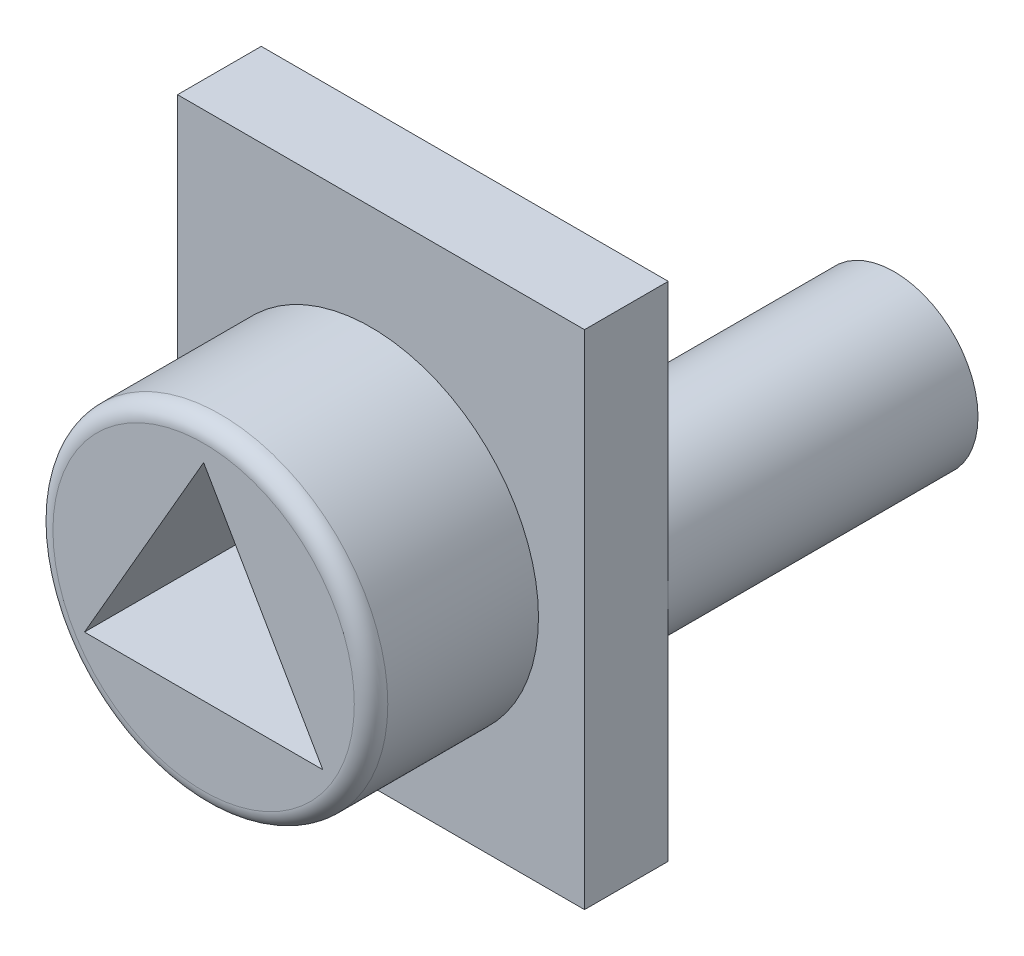
SolidWorks part; units mm, degrees
ref_plane "Спереди" through (0, 0, 0) normal (0, 0, 1) x (1, 0, 0)
ref_plane "Сверху" through (0, 0, 0) normal (0, 1, 0) x (1, 0, 0)
ref_plane "Справа" through (0, 0, 0) normal (1, 0, 0) x (0, 0, -1)
other "Configuration Table"
sketch "Эскиз1" plane through (0, 0, 0) normal (0, 0, 1) x (1, 0, 0)
  line L0 (-2.7384, -2.0301) -> (2.2616, -2.0301)
  line L1 (4.8616, -6) -> (4.8616, 6)
  line L2 (4.8616, 6) -> (-4.8616, 6)
  line L3 (-4.8616, 6) -> (-4.8616, -6)
  line L4 (-4.8616, -6) -> (4.8616, -6)
  line L5 (-0.2384, 2.3) -> (-2.7384, -2.0301)
  line L6 (2.2616, -2.0301) -> (-0.2384, 2.3)
  circle A0 centre (-0.2384, -0.5) radius 4
  circle A1 centre (2.8616, -0.5) radius 2
sketch "Эскиз2" plane through (0, 0, 0) normal (0, 0, 1) x (1, 0, 0)
  line L0 (-4.8616, -6) -> (4.8616, -6) construction
  line L1 (-4.8616, 6) -> (-4.8616, -6) construction
  line L2 (4.8616, 6) -> (-4.8616, 6) construction
  line L3 (4.8616, -6) -> (4.8616, 6) construction
  line L4 (-4.8616, -6) -> (4.8616, -6)
  line L5 (-4.8616, 6) -> (-4.8616, -6)
  line L6 (4.8616, 6) -> (-4.8616, 6)
  line L7 (4.8616, -6) -> (4.8616, 6)
extrude "Бобышка-Вытянуть1" add sketch "Эскиз2" along normal blind 2
sketch "Эскиз3" plane through (0, 0, 2) normal (0, 0, 1) x (1, 0, 0)
  line L6 (-3.0848, -2.2301) -> (-0.2384, 2.7)
  line L7 (-0.2384, 2.7) -> (2.608, -2.2301)
  line L8 (2.608, -2.2301) -> (-3.0848, -2.2301)
  line L9 (-0.2384, 2.3) -> (-2.7384, -2.0301) construction
  line L10 (2.2616, -2.0301) -> (-0.2384, 2.3) construction
  line L11 (-2.7384, -2.0301) -> (2.2616, -2.0301) construction
  circle A0 centre (-0.2384, -0.5) radius 4 construction
  circle A1 centre (-0.2384, -0.5) radius 4
  dimension "D1" = 0.2
  dimension "D2" = 0.2
  dimension "D3" = 0.2
extrude "Бобышка-Вытянуть2" add sketch "Эскиз3" along normal blind 4
sketch "Эскиз4" plane through (0, 0, 0) normal (0, 0, -1) x (-1, 0, 0)
  circle A0 centre (-2.8616, -0.5) radius 2 construction
  circle A1 centre (-2.8616, -0.5) radius 2
extrude "Бобышка-Вытянуть3" add sketch "Эскиз4" along normal blind 7.4
fillet "Скругление1" radius 0.4 1 edges at (3.7616, -0.5, 6)
sketch "hole" plane through (0, 0, 6) normal (0, 0, 1) x (1, 0, 0)
  line L0 (-3.0848, -2.2301) -> (2.608, -2.2301) construction
  line L1 (2.608, -2.2301) -> (-0.2384, 2.7) construction
  line L2 (-0.2384, 2.7) -> (-3.0848, -2.2301) construction
  line L3 (-3.0848, -2.2301) -> (2.608, -2.2301)
  line L4 (2.608, -2.2301) -> (-0.2384, 2.7)
  line L5 (-0.2384, 2.7) -> (-3.0848, -2.2301)
sketch "Эскиз5" plane through (0, 0, 2) normal (0, 0, 1) x (1, 0, 0)
  line L0 (2.608, -2.2301) -> (-0.2384, 2.7) construction
  line L1 (-0.2384, 2.7) -> (-3.0848, -2.2301) construction
  circle A0 centre (-0.2384, -0.58) radius 1.1
  dimension "D1" = 2.2
  dimension "D2" = 1.64
  dimension "D3" = 1.64
extrude "Вырез-Вытянуть1" cut sketch "Эскиз5" against normal blind 2
